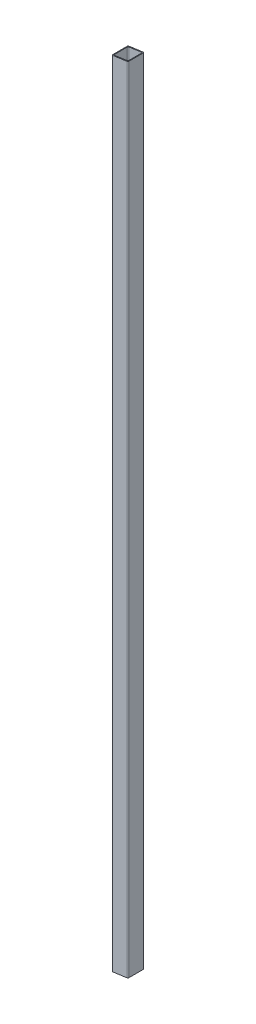
SolidWorks part; units mm, degrees
material "1.0116 (S235J2G3)"
ref_plane "Front Plane" through (0, 0, 0) normal (0, 0, 1) x (1, 0, 0)
ref_plane "Top Plane" through (0, 0, 0) normal (0, 1, 0) x (1, 0, 0)
ref_plane "Right Plane" through (0, 0, 0) normal (1, 0, 0) x (0, 0, -1)
sketch "Sketch1" plane through (0, 0, 0) normal (0, 1, 0) x (1, 0, 0)
  line L1 (5, 0) -> (95, 0)
  line L2 (0, -5) -> (0, -95)
  line L3 (5, -100) -> (95, -100)
  line L4 (100, -5) -> (100, -95)
  line L5 (10, -5) -> (90, -5)
  line L6 (5, -10) -> (5, -90)
  line L7 (10, -95) -> (90, -95)
  line L8 (95, -10) -> (95, -90)
  arc A0 (10, -95) -> (5, -90) centre (10, -90) cw
  arc A1 (10, -5) -> (5, -10) centre (10, -10) ccw
  arc A2 (100, -5) -> (95, 0) centre (95, -5) ccw
  arc A3 (100, -95) -> (95, -100) centre (95, -95) cw
  arc A4 (5, -100) -> (0, -95) centre (5, -95) cw
  arc A5 (5, 0) -> (0, -5) centre (5, -5) ccw
  arc A6 (95, -90) -> (90, -95) centre (90, -90) cw
  arc A7 (90, -5) -> (95, -10) centre (90, -10) cw
  point P9 (50, -95)
  point P16 (100, 0)
  point P21 (0, -100)
  point P24 (0, 0)
  dimension "D7" = 5
  dimension "D8" = 5
  dimension "D1" = 100
  dimension "D2" = 100
  dimension "D3" = 5
  dimension "D4" = 5
  dimension "D5" = 5
  dimension "D6" = 5
extrude "Boss-Extrude1" add sketch "Sketch1" along normal blind 4950
sketch "Sketch2" plane through (0, 0, 0) normal (0, 0, -1) x (-1, 0, 0)
  line L1 (-100, 14.0541) -> (0, 0)
  line L2 (0, 0) -> (-100, 0)
  line L3 (-100, 0) -> (-100, 14.0541)
  line L4 (-238.7113, 500) -> (182.2276, 500) construction
  line L5 (-100, 4950) -> (0, 4935.9459)
  line L6 (-100, 4935.9459) -> (-100, 4950)
  line L7 (-100, 4935.9459) -> (0, 4935.9459)
  line L8 (-100, 4950) -> (0, 4950)
  line L9 (0, 4950) -> (0, 4935.9459)
  line M5 (-5, 0) -> (-5, 4950)
  line M6 (-5, 4950) -> (-95, 4950)
  line M7 (-95, 4950) -> (-95, 0)
  dimension "D1" = 100
  dimension "D2" = 8
  dimension "D3" = 0
  dimension "D4" = 500
  dimension "D5" = 4950
  dimension "D6" = 100
  dimension "D7" = 100
  dimension "D8" = 8
  dimension "D9" = 100
extrude "Cut-Extrude1" cut sketch "Sketch2" against normal blind 1000 contours L5 M7 M5 M6 | L9 L8 L5 M5 | L8 L5 M7 | L3 L1 L2
